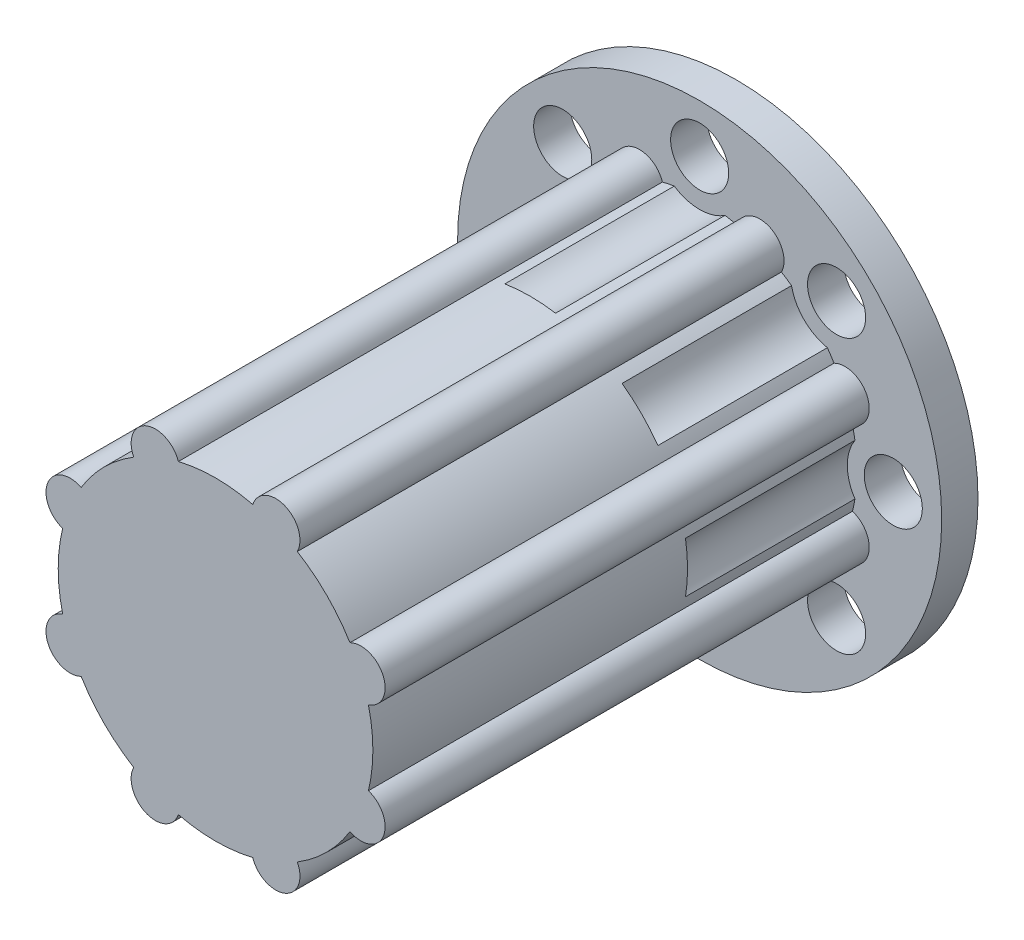
SolidWorks part; units mm, degrees
ref_plane "Alzado" through (0, 0, 0) normal (0, 0, 1) x (1, 0, 0)
ref_plane "Planta" through (0, 0, 0) normal (0, 1, 0) x (1, 0, 0)
ref_plane "Vista lateral" through (0, 0, 0) normal (1, 0, 0) x (0, 0, -1)
sketch "Croquis1" plane through (0, 0, 0) normal (0, 0, 1) x (1, 0, 0)
  circle A0 centre (1.4679, 11.2007) radius 10
  circle A1 centre (1.4679, 11.2007) radius 5
  dimension "D1" = 20
  dimension "D2" = 10
extrude "Saliente-Extruir1" add sketch "Croquis1" against normal blind 1.5 contours A0 | A1
sketch "Croquis2" plane through (0, 0, 0) normal (0, 0, 1) x (1, 0, 0)
  circle A0 centre (1.4679, 11.2007) radius 8 construction
  circle A1 centre (1.4679, 19.2007) radius 1.2
  circle A2 centre (7.1248, 16.8575) radius 1.2
  circle A3 centre (9.4679, 11.2007) radius 1.2
  circle A4 centre (7.1248, 5.5438) radius 1.2
  circle A5 centre (1.4679, 3.2007) radius 1.2
  circle A6 centre (-4.1889, 5.5438) radius 1.2
  circle A7 centre (-6.5321, 11.2007) radius 1.2
  circle A8 centre (-4.1889, 16.8575) radius 1.2
  dimension "D1" = 8
  dimension "D2" = 2.4
  dimension "D3" = 8
extrude "Cortar-Extruir1" cut sketch "Croquis2" against normal up to next
sketch "Croquis3" plane through (0, 0, 0) normal (0, 0, 1) x (1, 0, 0)
  circle A0 centre (1.4679, 11.2007) radius 6.5
  circle A1 centre (1.4679, 11.2007) radius 5
  dimension "D1" = 13
  dimension "D2" = 10
extrude "Saliente-Extruir2" add sketch "Croquis3" along normal blind 20
sketch "Croquis5" plane through (0, 0, 20) normal (0, 0, 1) x (1, 0, 0)
  line L1 (9.5859, 11.2007) -> (7.2082, 16.9409) construction
  line L2 (7.2082, 16.9409) -> (1.4679, 19.3186) construction
  line L3 (1.4679, 19.3186) -> (-4.2723, 16.9409) construction
  line L4 (-4.2723, 16.9409) -> (-6.65, 11.2007) construction
  line L5 (-6.65, 11.2007) -> (-4.2723, 5.4604) construction
  line L6 (-4.2723, 5.4604) -> (1.4679, 3.0827) construction
  line L7 (1.4679, 3.0827) -> (7.2082, 5.4604) construction
  line L8 (7.2082, 5.4604) -> (9.5859, 11.2007) construction
  circle A11 centre (1.4679, 11.2007) radius 7.5 construction
  circle A12 centre (3.9554, 17.2059) radius 1
  circle A13 centre (1.4679, 11.2007) radius 6.5 construction
  circle A14 centre (7.4732, 13.6881) radius 1
  circle A15 centre (7.4732, 8.7132) radius 1
  circle A16 centre (3.9554, 5.1955) radius 1
  circle A17 centre (-1.0195, 5.1955) radius 1
  circle A18 centre (-4.5373, 8.7132) radius 1
  circle A19 centre (-4.5373, 13.6881) radius 1
  circle A20 centre (-1.0195, 17.2059) radius 1
  dimension "D1" = 2
  dimension "D2" = 8
  dimension "D3" = 15
extrude "Saliente-Extruir3" add sketch "Croquis5" against normal up to surface (20 mm away) up to face at (11.4679, 11.2007, 0)
sketch "Croquis7" plane through (0, 0, 0) normal (0, 0, 1) x (1, 0, 0)
  circle A0 centre (7.1248, 16.8575) radius 1.2 construction
  circle A1 centre (9.4679, 11.2007) radius 1.2 construction
  circle A2 centre (7.1248, 5.5438) radius 1.2 construction
  circle A3 centre (1.4679, 3.2007) radius 1.2 construction
  circle A4 centre (-4.1889, 5.5438) radius 1.2 construction
  circle A5 centre (-6.5321, 11.2007) radius 1.2 construction
  circle A6 centre (-4.1889, 16.8575) radius 1.2 construction
  circle A7 centre (1.4679, 19.2007) radius 1.2 construction
  circle A8 centre (7.1248, 16.8575) radius 1.2 construction
  circle A9 centre (9.4679, 11.2007) radius 1.2 construction
  circle A10 centre (7.1248, 5.5438) radius 1.2 construction
  circle A11 centre (1.4679, 3.2007) radius 1.2 construction
  circle A12 centre (-4.1889, 5.5438) radius 1.2 construction
  circle A13 centre (-6.5321, 11.2007) radius 1.2 construction
  circle A14 centre (-4.1889, 16.8575) radius 1.2 construction
  circle A15 centre (1.4679, 19.2007) radius 1.2 construction
  circle A16 centre (-4.1889, 16.8575) radius 1.9
  circle A17 centre (1.4679, 19.2007) radius 1.9
  circle A18 centre (7.1248, 16.8575) radius 1.9
  circle A19 centre (9.4679, 11.2007) radius 1.9
  circle A20 centre (7.1248, 5.5438) radius 1.9
  circle A21 centre (1.4679, 3.2007) radius 1.9
  circle A22 centre (-4.1889, 5.5438) radius 1.9
  circle A23 centre (-6.5321, 11.2007) radius 1.9
  dimension "D1" = 0.7
extrude "Cortar-Extruir3" cut sketch "Croquis7" along normal blind 7
sketch "Croquis8" plane through (0, 0, 20) normal (0, 0, 1) x (1, 0, 0)
  circle A0 centre (1.4679, 11.2007) radius 6
  dimension "D1" = 12
extrude "Saliente-Extruir4" add sketch "Croquis8" against normal blind 15
